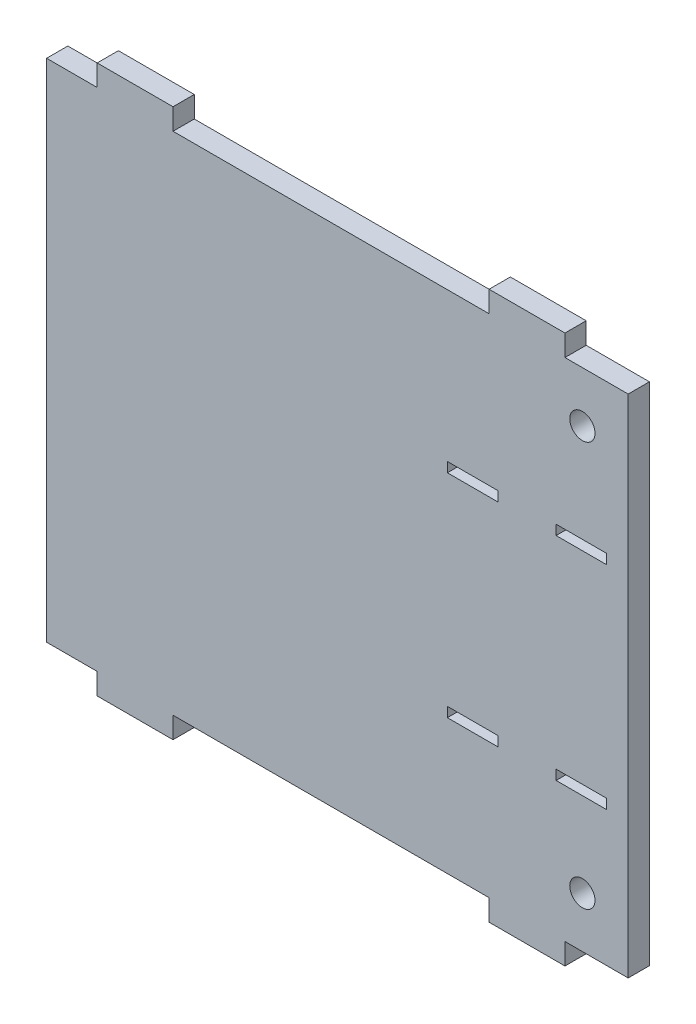
SolidWorks part; units mm, degrees
ref_plane "Front Plane" through (0, 0, 0) normal (0, 0, 1) x (1, 0, 0)
ref_plane "Top Plane" through (0, 0, 0) normal (0, 1, 0) x (1, 0, 0)
ref_plane "Right Plane" through (0, 0, 0) normal (1, 0, 0) x (0, 0, -1)
sketch "Sketch1" plane through (0, 0, 0) normal (0, 0, 1) x (1, 0, 0)
  line L1 (-25.4, 63.5) -> (25.4, 63.5)
  line L2 (-25.4, 63.5) -> (-25.4, -63.5)
  line L3 (-25.4, -63.5) -> (25.4, -63.5)
  line L4 (25.4, 63.5) -> (25.4, -63.5)
  line L5 (-25.4, 63.5) -> (25.4, -63.5) construction
  line L6 (-25.4, -63.5) -> (25.4, 63.5) construction
  point P0 (0, 0)
  dimension "D1" = 127
  dimension "D2" = 50.8
extrude "body" add sketch "Sketch1" along normal blind 5.334
sketch "Sketch3" plane through (0, 63.5, 0) normal (0, 1, 0) x (1, 0, 0)
  line L0 (0, 0) -> (0, -50000) construction
  line L1 (25.4, -5.334) -> (-25.4, -5.334) construction
  line L2 (-9.525, 0) -> (9.525, 0)
  line L3 (-9.525, 0) -> (-9.525, -5.334)
  line L4 (-9.525, -5.334) -> (9.525, -5.334)
  line L5 (9.525, 0) -> (9.525, -5.334)
  line L6 (-9.525, 0) -> (9.525, -5.334) construction
  line L7 (-9.525, -5.334) -> (9.525, 0) construction
  line L8 (9.525, 11.7572) -> (25.4, 11.7572) construction
  point P3 (0, -2.667)
  dimension "D1" = 19.05
  dimension "D2" = 15.875
extrude "Top tab" add sketch "Sketch3" along normal blind 5.334
sketch "Sketch4" plane through (0, -63.5, 0) normal (0, -1, 0) x (1, 0, 0)
  line L0 (0, 0) -> (0, -50000) construction
  line L1 (-25.4, 0) -> (25.4, 0) construction
  line L2 (-9.525, 5.334) -> (9.525, 5.334)
  line L3 (-9.525, 5.334) -> (-9.525, 0)
  line L4 (-9.525, 0) -> (9.525, 0)
  line L5 (9.525, 5.334) -> (9.525, 0)
  line L6 (-9.525, 5.334) -> (9.525, 0) construction
  line L7 (-9.525, 0) -> (9.525, 5.334) construction
  point P3 (0, 2.667)
  dimension "D1" = 19.05
extrude "Bot tab" add sketch "Sketch4" along normal blind 5.334
sketch "Sketch5" plane through (0, 0, 5.334) normal (0, 0, 1) x (1, 0, 0)
  line L0 (0, 0) -> (0, -50000) construction
  line L1 (-20, 26.1412) -> (-7.3, 26.1412)
  line L2 (-20, 26.1412) -> (-20, 23.6774)
  line L3 (-20, 23.6774) -> (-7.3, 23.6774)
  line L4 (-7.3, 26.1412) -> (-7.3, 23.6774)
  line L5 (7.3, -27.1226) -> (7.3, -29.5864)
  line L6 (20, -29.5864) -> (7.3, -29.5864)
  line L7 (20, -27.1226) -> (20, -29.5864)
  line L8 (20, -27.1226) -> (7.3, -27.1226)
  line L9 (-20, -27.1226) -> (-7.3, -27.1226)
  line L10 (-20, -27.1226) -> (-20, -29.5864)
  line L11 (-20, -29.5864) -> (-7.3, -29.5864)
  line L12 (-7.3, -27.1226) -> (-7.3, -29.5864)
  line L13 (7.3, 26.1412) -> (7.3, 23.6774)
  line L14 (20, 23.6774) -> (7.3, 23.6774)
  line L15 (20, 26.1412) -> (20, 23.6774)
  line L16 (20, 26.1412) -> (7.3, 26.1412)
  dimension "D1" = 37.3588
  dimension "D2" = 33.9136
  dimension "D3" = 5.4
  dimension "D4" = 5.4
  dimension "D5" = 2.4638
  dimension "D6" = 2.4638
  dimension "D7" = 12.7
  dimension "D8" = 12.7
extrude "middle cuts" cut sketch "Sketch5" against normal through all
sketch "Sketch6" plane through (0, 0, 5.334) normal (0, 0, 1) x (1, 0, 0)
  line L0 (25.4, 0) -> (13.9, 0) construction
  line L1 (25.4, -63.5) -> (25.4, 63.5) construction
  line L2 (13.9, 0) -> (13.9, 50.8) construction
  circle A0 centre (13.9, 50.8) radius 3.175
  circle A1 centre (13.9, -50.8) radius 3.175
  dimension "D3" = 6.35
  dimension "D1" = 50.8
  dimension "D2" = 11.5
extrude "BoltHoles" cut sketch "Sketch6" against normal through all
sketch "Sketch8" plane through (-25.4, 0, 0) normal (-1, 0, 0) x (0, 0, 1)
  line L0 (5.334, 63.5) -> (5.334, -63.5) construction
  line L1 (0, 63.5) -> (5.334, 63.5)
  line L2 (0, 63.5) -> (0, -63.5)
  line L3 (0, -63.5) -> (5.334, -63.5)
  line L4 (5.334, 63.5) -> (5.334, -63.5)
  line L5 (5.334, -63.5) -> (0, -63.5) construction
extrude "PIC platform" add sketch "Sketch8" along normal blind 95.25
sketch "Sketch10" plane through (0, 63.5, 0) normal (0, 1, 0) x (1, 0, 0)
  line L0 (-9.525, 0) -> (-120.65, 0) construction
  line L1 (-107.95, 0) -> (-88.9, 0)
  line L2 (-107.95, 0) -> (-107.95, -5.334)
  line L3 (-107.95, -5.334) -> (-88.9, -5.334)
  line L4 (-88.9, 0) -> (-88.9, -5.334)
  line L5 (-9.525, -5.334) -> (-120.65, -5.334) construction
  dimension "D1" = 12.7
  dimension "D2" = 19.05
extrude "LeftExtrude" add sketch "Sketch10" along normal blind 5.334
sketch "Sketch11" plane through (0, -63.5, 0) normal (0, -1, 0) x (1, 0, 0)
  line L0 (-120.65, 5.334) -> (-9.525, 5.334) construction
  line L1 (-107.95, 5.334) -> (-88.9, 5.334)
  line L2 (-107.95, 5.334) -> (-107.95, 0)
  line L3 (-107.95, 0) -> (-88.9, 0)
  line L4 (-88.9, 5.334) -> (-88.9, 0)
  line L5 (-120.65, 0) -> (-9.525, 0) construction
  dimension "D1" = 12.7
  dimension "D2" = 19.05
extrude "RightExtrude" add sketch "Sketch11" along normal blind 5.334
